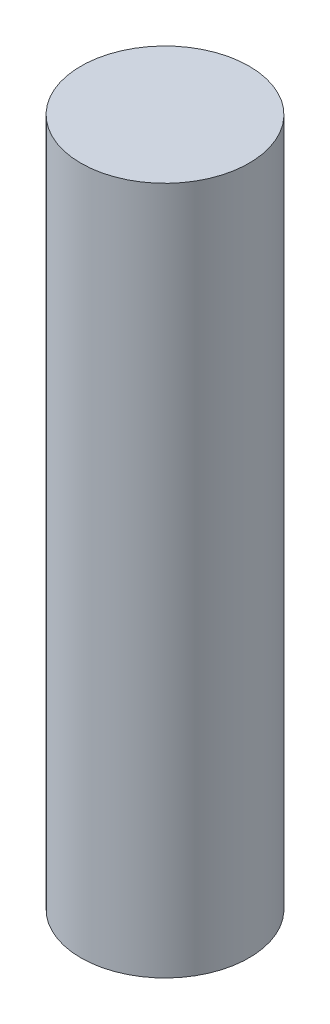
SolidWorks part; units mm, degrees
material "PBT General Purpose"
ref_plane "Front Plane" through (0, 0, 0) normal (0, 0, 1) x (1, 0, 0)
ref_plane "Top Plane" through (0, 0, 0) normal (0, 1, 0) x (1, 0, 0)
ref_plane "Right Plane" through (0, 0, 0) normal (1, 0, 0) x (0, 0, -1)
sketch "Sketch1" plane through (0, 0, 0) normal (0, 1, 0) x (1, 0, 0)
  circle A0 centre (0, 0) radius 27.5
extrude "Boss-Extrude1" add sketch "Sketch1" along normal blind 225
